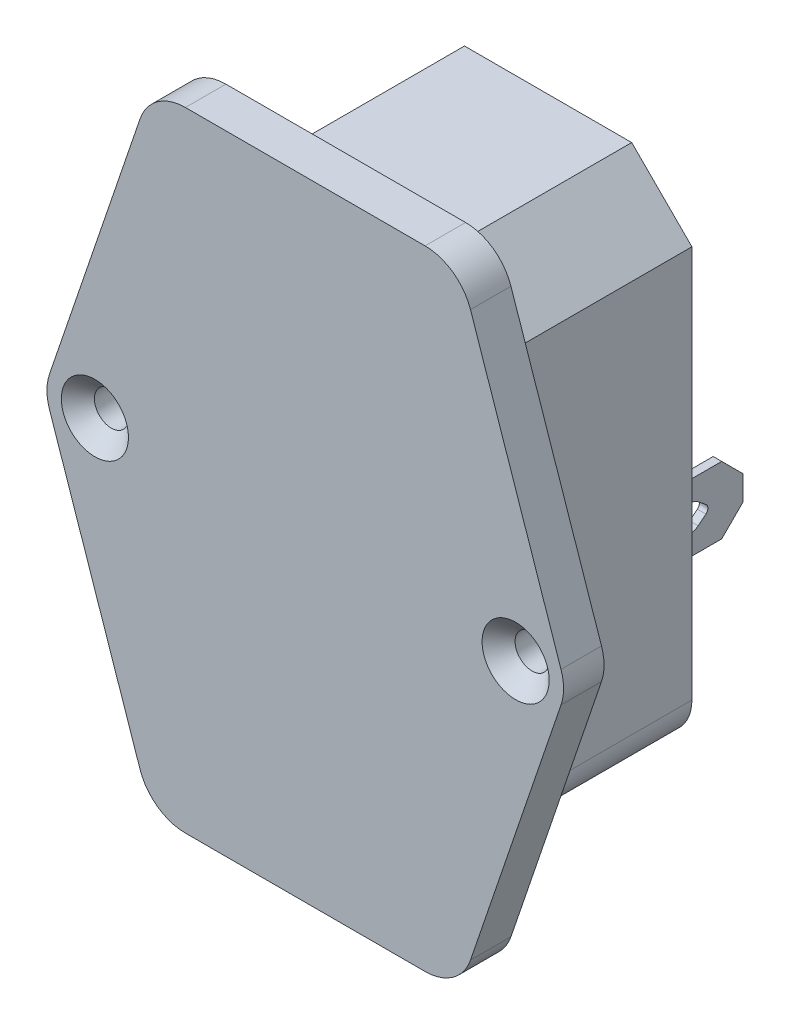
SolidWorks part; units mm, degrees
ref_plane "Front" through (0, 0, 0) normal (0, 0, 1) x (1, 0, 0)
ref_plane "Top" through (0, 0, 0) normal (0, 1, 0) x (1, 0, 0)
ref_plane "Right" through (0, 0, 0) normal (1, 0, 0) x (0, 0, -1)
sketch "Sketch1" plane through (0, 0, 0) normal (0, 0, 1) x (1, 0, 0)
  line L1 (0, 0) -> (27, 0)
  line L2 (0, 0) -> (0, 46.5)
  line L3 (0, 46.5) -> (27, 46.5)
  line L4 (27, 0) -> (27, 46.5)
  dimension "D1" = 27
  dimension "D2" = 46.5
extrude "Boss-Extrude1" add sketch "Sketch1" along normal blind 19
sketch "Sketch2" plane through (0, 0, 19) normal (0, 0, 1) x (1, 0, 0)
  line L0 (2.25, -7.8) -> (24.75, -7.8)
  line L1 (24.75, 51.2) -> (2.25, 51.2)
  line L2 (-2.0105, 48.1486) -> (-10.5105, 23.1486)
  line L3 (-10.5105, 20.2514) -> (-2.0105, -4.7486)
  line L4 (29.0105, -4.7486) -> (37.5105, 20.2514)
  line L5 (37.5105, 23.1486) -> (29.0105, 48.1486)
  line L6 (27.973, 51.2) -> (27.973, -7.8) construction
  line L7 (-0.973, 51.2) -> (-0.973, -7.8) construction
  line L8 (27, 46.5) -> (0, 46.5) construction
  line L9 (0, 46.5) -> (-0.973, 46.5) construction
  line L10 (27, 46.5) -> (27.973, 46.5) construction
  line L11 (38.003, 21.7) -> (27.973, 21.7) construction
  line L12 (-0.973, 21.7) -> (-11.003, 21.7) construction
  arc A0 (37.5105, 20.2514) -> (37.5105, 23.1486) centre (33.25, 21.7) ccw
  arc A1 (-10.5105, 23.1486) -> (-10.5105, 20.2514) centre (-6.25, 21.7) ccw
  circle A2 centre (-6.25, 21.7) radius 1.6
  circle A3 centre (33.25, 21.7) radius 1.6
  arc A4 (2.25, -7.8) -> (-2.0105, -4.7486) centre (2.25, -3.3) cw
  arc A5 (24.75, -7.8) -> (29.0105, -4.7486) centre (24.75, -3.3) ccw
  arc A6 (24.75, 51.2) -> (29.0105, 48.1486) centre (24.75, 46.7) cw
  arc A7 (2.25, 51.2) -> (-2.0105, 48.1486) centre (2.25, 46.7) ccw
  dimension "D3" = 4.5
  dimension "D4" = 3.2
  dimension "D5" = 39.5
  dimension "D6" = 4.5
  dimension "D1" = 59
  dimension "D2" = 4.7
  dimension "D7" = 22.5
extrude "Boss-Extrude2" add sketch "Sketch2" along normal blind 3.8
hole_wizard "CSK for M3 Flat Head Machine Screw1" positions "Sketch3" profile "Sketch4" countersink size "M3" standard "ANSI Metric" end condition through all
sketch "Sketch3" plane through (0, 0, 22.8) normal (0, 0, 1) x (1, 0, 0)
  point P0 (-6.25, 21.7)
  point P3 (33.25, 21.7)
sketch "Sketch4" plane through (-6.25, 21.7, 22.8) normal (1, 0, 0) x (0, -1, 0)
  line L0 (0, 0) -> (0, 22.8)
  line L1 (0, 22.8) -> (1.6, 22.8)
  line L2 (1.6, 22.8) -> (1.6, 1.55)
  line L3 (1.6, 1.55) -> (3.15, 0)
  line L5 (3.15, 0) -> (0, 0)
  line L6 (-1.6, 1.55) -> (-3.15, 0) construction
  line L11 (0, -6.35) -> (0, 107.95) construction
  dimension "Thru Hole Dia." = 3.2
  dimension "Thru Hole Depth" = 22.8
  dimension "Near C'Sink Dia." = 6.3
  dimension "Near C'Sink Angle" = 90
sketch "Sketch5" plane through (0, 0, 0) normal (0, 0, -1) x (-1, 0, 0)
  line L0 (-13.5, 0) -> (-13.5, 6.8546) construction
  line L1 (-22.6, 16.8) -> (-17.1, 16.8)
  line L2 (-22.6, 16.8) -> (-22.6, 7.5)
  line L3 (-22.6, 7.5) -> (-17.1, 7.5)
  line L4 (-17.1, 16.8) -> (-17.1, 7.5)
  line L5 (0, 0) -> (-27, 0) construction
  line L6 (-4.4, 7.5) -> (-9.9, 7.5)
  line L7 (-9.9, 16.8) -> (-9.9, 7.5)
  line L8 (-4.4, 16.8) -> (-9.9, 16.8)
  line L9 (-4.4, 16.8) -> (-4.4, 7.5)
  line L10 (0, 0) -> (-27, 0) construction
  dimension "D1" = 9.3
  dimension "D2" = 5.5
  dimension "D3" = 7.5
  dimension "D4" = 3.6
extrude "Boss-Extrude3" add sketch "Sketch5" along normal blind 2.5
ref_plane "Plane1" through (0, 5, 0) normal (0, -1, 0) x (-1, 0, 0)
sketch "Sketch6" plane through (0, 5, 0) normal (0, -1, 0) x (-1, 0, 0)
  line L0 (-13.5, 0) -> (-13.5, 11.5) construction
  line L1 (0, 0) -> (-27, 0) construction
  line L2 (-17.435, 0) -> (-17.435, 2.87)
  line L3 (-17.435, 2.87) -> (-16.65, 2.87)
  line L4 (-16.65, 2.87) -> (-16.65, 11.5)
  line L5 (-16.65, 11.5) -> (-10.35, 11.5)
  line L6 (-9.565, 0) -> (-9.565, 2.87)
  line L7 (-9.565, 2.87) -> (-10.35, 2.87)
  line L8 (-10.35, 2.87) -> (-10.35, 11.5)
  line L9 (-17.435, 0) -> (-9.565, 0)
  line L10 (-13.5, 8.5) -> (-14.4758, 7.2812)
  line L11 (-13.5, 8.5) -> (-12.5242, 7.2812)
  line L12 (-13.5, 6.5) -> (-13.5, 8.5) construction
  circle A0 centre (-13.5, 6.5) radius 1.25 construction
  arc A1 (-14.4758, 7.2812) -> (-12.5242, 7.2812) centre (-13.5, 6.5) ccw
  point P19 (-13.5, 8.5)
  dimension "D5" = 1.25
  dimension "D6" = 2
  dimension "D1" = 7.87
  dimension "D2" = 2.87
  dimension "D3" = 11.5
  dimension "D4" = 6.3
  dimension "D7" = 5
extrude "Boss-Extrude4" add sketch "Sketch6" along normal blind 0.8 separate body
chamfer "Chamfer1" distance 2 angle 45 2 edges at (16.65, 4.6, -11.5) (10.35, 4.6, -11.5)
fillet "Fillet1" radius 0.5 1 edges at (13.5, 4.6, -8.5)
ref_plane "Plane2" through (13.5, 0, 0) normal (1, 0, 0) x (0, 0, -1)
ref_plane "Plane3" through (19.5, 0, 0) normal (1, 0, 0) x (0, 0, -1)
sketch "Sketch7" plane through (19.5, 0, 0) normal (1, 0, 0) x (0, 0, -1)
  line L0 (2.5, 12.15) -> (11.5, 12.15) construction
  line L1 (2.5, 16.8) -> (2.5, 7.5) construction
  line L2 (11.5, 9) -> (11.5, 15.3)
  line L3 (11.5, 15.3) -> (2.5, 15.3)
  line L4 (11.5, 9) -> (2.5, 9)
  line L5 (2.5, 15.3) -> (2.5, 9)
  line L6 (11.5, 5) -> (11.5, 4.2) construction
  line L7 (7.2812, 13.1258) -> (8.5, 12.15)
  line L8 (8.5, 12.15) -> (7.2812, 11.1742)
  circle A0 centre (6.5, 12.15) radius 1.25 construction
  arc A1 (7.2812, 13.1258) -> (7.2812, 11.1742) centre (6.5, 12.15) ccw
  point P18 (8.5, 12.15)
  dimension "D2" = 2
  dimension "D3" = 1.25
  dimension "D1" = 6.3
  dimension "D4" = 5
extrude "Boss-Extrude5" add sketch "Sketch7" along normal blind 0.8 separate body
chamfer "Chamfer2" distance 2 angle 45 2 edges at (19.9, 15.3, -11.5) (19.9, 9, -11.5)
fillet "Fillet3" radius 0.5 1 edges at (19.9, 12.15, -8.5)
mirror "Mirror2" about plane through (13.5, 0, 0) normal (1, 0, 0) of bodies 106
chamfer "Chamfer3" distance 5.65 2 edges at (27, 46.5, 9.5) (0, 46.5, 9.5)
fillet "Fillet2" radius 4 2 edges at (0, 0, 9.5) (27, 0, 9.5)
